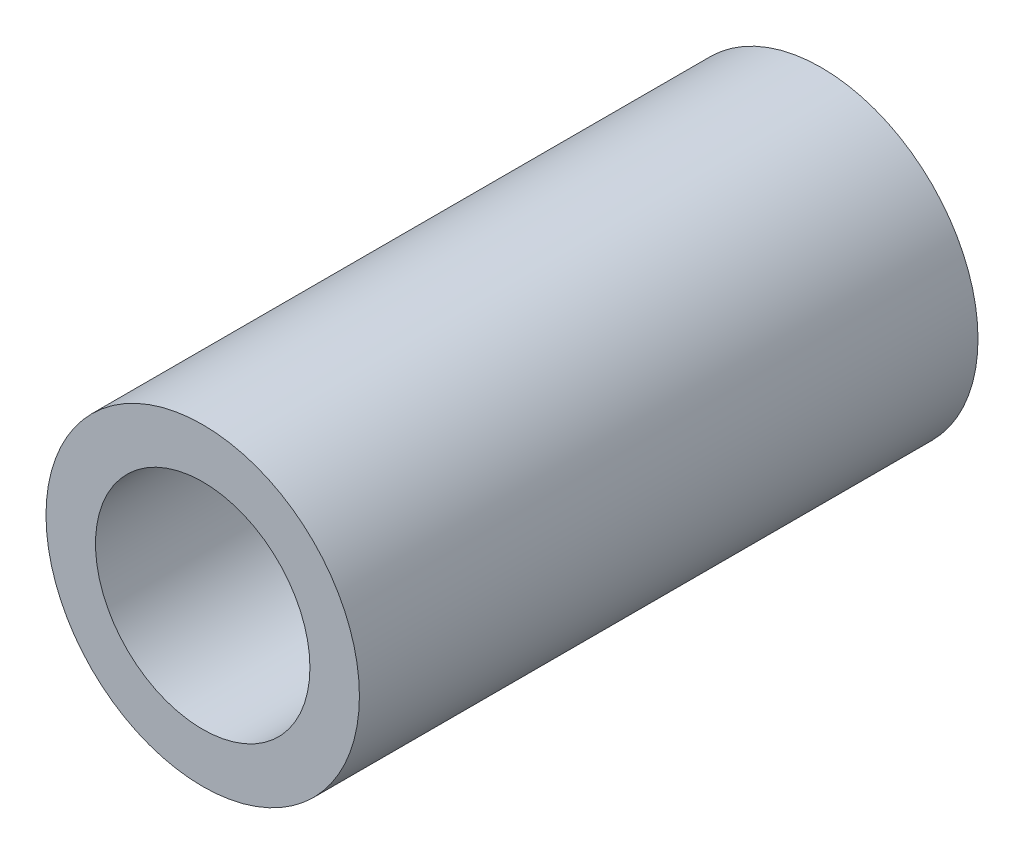
SolidWorks part; units mm, degrees
ref_plane "Alzado" through (0, 0, 0) normal (0, 0, 1) x (1, 0, 0)
ref_plane "Planta" through (0, 0, 0) normal (0, 1, 0) x (1, 0, 0)
ref_plane "Vista lateral" through (0, 0, 0) normal (1, 0, 0) x (0, 0, -1)
sketch "Croquis1" plane through (0, 0, 0) normal (0, 0, 1) x (1, 0, 0)
  circle A0 centre (-72.6768, 18.2388) radius 2.6
  circle A1 centre (-72.6768, 18.2388) radius 3.8
extrude "Saliente-Extruir1" add sketch "Croquis1" along normal blind 15
